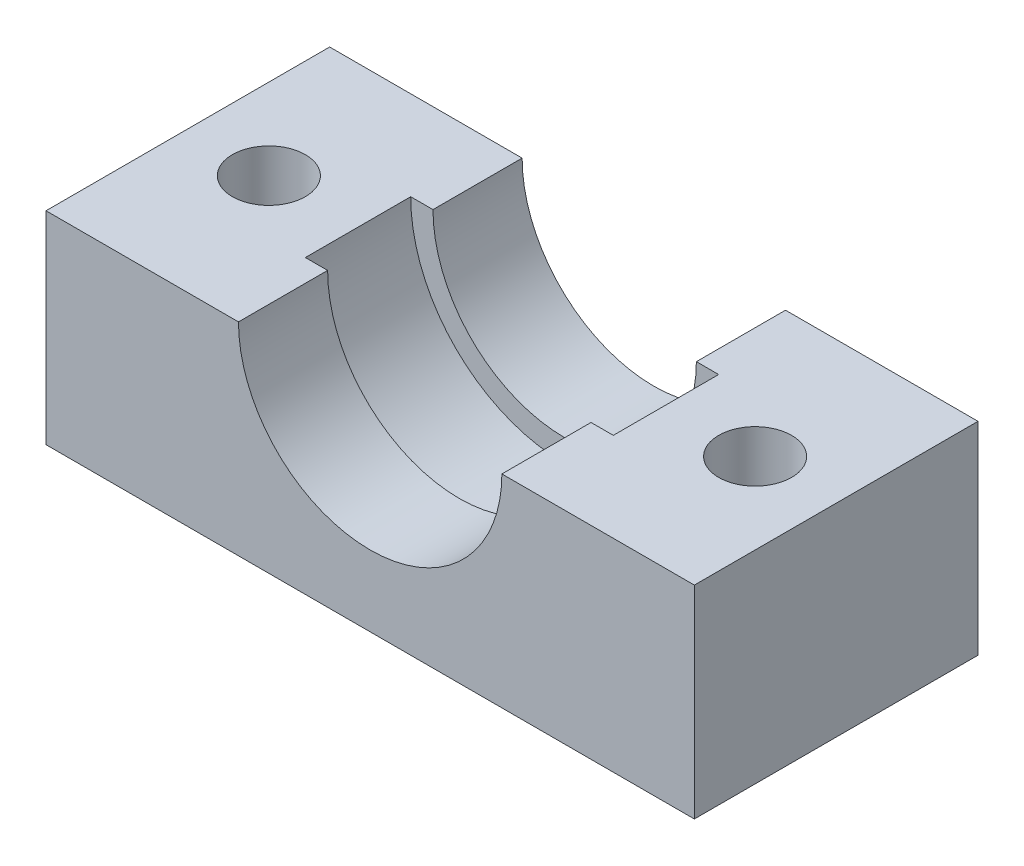
SolidWorks part; units mm, degrees
ref_plane "前基準面" through (0, 0, 0) normal (0, 0, 1) x (1, 0, 0)
ref_plane "上基準面" through (0, 0, 0) normal (0, 1, 0) x (1, 0, 0)
ref_plane "右基準面" through (0, 0, 0) normal (1, 0, 0) x (0, 0, -1)
sketch "草圖1" plane through (0, 0, 0) normal (0, 1, 0) x (1, 0, 0)
  line L1 (-16, -7) -> (16, -7)
  line L2 (-16, -7) -> (-16, 7)
  line L3 (-16, 7) -> (16, 7)
  line L4 (16, -7) -> (16, 7)
  line L5 (-16, -7) -> (16, 7) construction
  line L6 (-16, 7) -> (16, -7) construction
  point P0 (0, 0)
  dimension "D1" = 32
  dimension "D2" = 14
extrude "填料-伸長1" add sketch "草圖1" along normal blind 10
sketch "草圖2" plane through (0, 0, 0) normal (0, 0, 1) x (1, 0, 0)
  line L0 (0, 10) -> (0, 0) construction
  line L1 (-16, 0) -> (16, 0) construction
  line L2 (16, 10) -> (-16, 10) construction
  circle A0 centre (0, 10) radius 7.6
  dimension "D1" = 15.2
extrude "除料-伸長1" cut sketch "草圖2" against normal mid plane 5.2
sketch "草圖3" plane through (0, 0, 0) normal (0, 0, 1) x (1, 0, 0)
  circle A0 centre (0, 10) radius 6.5
  dimension "D1" = 13
extrude "除料-伸長2" cut sketch "草圖3" against normal through all both and the other way through all
sketch "草圖4" plane through (0, 10, 0) normal (0, 1, 0) x (1, 0, 0)
  line L0 (-12, 0) -> (0, 0) construction
  line L1 (0, 0) -> (0, 18.2075) construction
  circle A0 centre (-12, 0) radius 1
  circle A1 centre (12, 0) radius 1
  dimension "D2" = 2
  dimension "D1" = 24
extrude "除料-伸長3" cut sketch "草圖4" against normal through all
hole_wizard "M3 六角承窩頭蓋螺釘的柱孔1" positions "草圖5" profile "草圖6" counterbore size "M3" standard "ISO" end condition up to next
sketch "草圖5" plane through (0, 0, 0) normal (0, -1, 0) x (-1, 0, 0)
  point P0 (-12, 0)
  point P2 (12, 0)
sketch "草圖6" plane through (12, 0, 0) normal (1, 0, 0) x (0, 0, -1)
  line L0 (0, 0) -> (0, 10)
  line L1 (0, 10) -> (1.8, 10)
  line L3 (1.8, 10) -> (1.8, 3.4)
  line L4 (1.8, 3.4) -> (3.25, 3.4)
  line L5 (3.25, 3.4) -> (3.25, 0)
  line L7 (3.25, 0) -> (0, 0)
  line L11 (0, -6.35) -> (0, 107.95) construction
  dimension "貫穿孔直徑" = 3.6
  dimension "貫穿孔深度" = 10
  dimension "柱孔直徑" = 6.5
  dimension "柱孔深度" = 3.4
sketch "草圖7" plane through (0, 0, 7) normal (0, 0, 1) x (1, 0, 0)
  line L0 (-6.5, 10) -> (-9.5, 10)
  line L1 (6.5, 10) -> (9.5, 10)
  arc A0 (-6.5, 10) -> (6.5, 10) centre (0, 10) ccw construction
  arc A1 (-6.5, 10) -> (6.5, 10) centre (0, 10) ccw
  arc A2 (-9.5, 10) -> (9.5, 10) centre (0, 10) ccw
  dimension "D1" = 3
extrude "填料-伸長2" [suppressed] add sketch "草圖7" along normal blind 18
